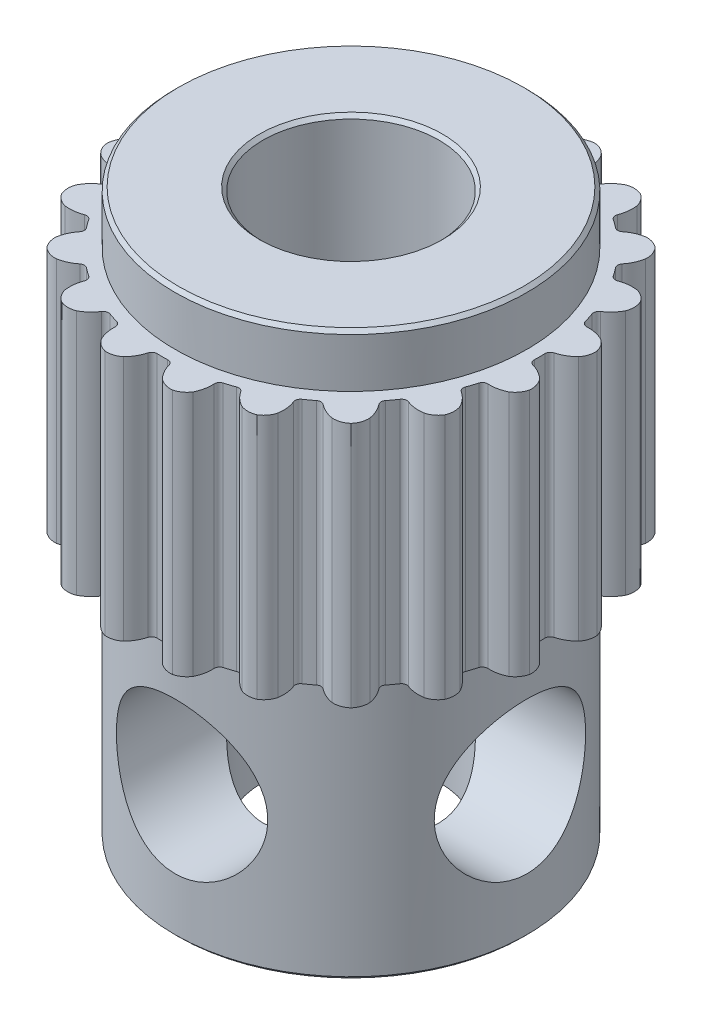
SolidWorks part; units mm, degrees
material "6061-T6 (SS)"
ref_plane "Front Plane" through (0, 0, 0) normal (0, 0, 1) x (1, 0, 0)
ref_plane "Top Plane" through (0, 0, 0) normal (0, 1, 0) x (1, 0, 0)
ref_plane "Right Plane" through (0, 0, 0) normal (1, 0, 0) x (0, 0, -1)
sketch "BodyS" plane through (0, 0, 0) normal (0, 0, 1) x (1, 0, 0)
  line L0 (6.11, -3.5) -> (6.11, 3.5)
  line L3 (6.11, 3.5) -> (2.5, 3.5)
  line L4 (2.5, 3.5) -> (2.5, -3.5)
  line L9 (2.5, -3.5) -> (6.11, -3.5)
  line L12 (0, 0) -> (6.11, 0) construction
  line L13 (0, 3.5) -> (0, -3.5) construction
  dimension "BoreDia" = 5
  dimension "Height" = 7
  dimension "BeltPathDiaControl" = 3.61
  dimension "RefBeltPathDia" = 12.22
revolve "Body" add sketch "BodyS" angle 360 about L13
sketch "GT2ProfileS" plane through (0, 0, 0) normal (0, 1, 0) x (1, 0, 0)
  line L1 (0, -6.11) -> (0, -5.36) construction
  line L2 (-0.9955, -6.0283) -> (-0.8733, -5.2884) construction
  line L3 (0, 0) -> (-0.8733, -5.2884) construction
  line L4 (0.9955, -6.0283) -> (0, 0) construction
  arc A3 (0.2997, -5.4688) -> (0.1507, -5.3579) centre (0.1549, -5.5078) ccw
  arc A4 (-0.9955, -6.0283) -> (0.9955, -6.0283) centre (0, 0) ccw
  arc A5 (-0.2997, -5.4688) -> (-0.1507, -5.3579) centre (-0.1549, -5.5078) cw
  arc A6 (-0.2997, -5.4688) -> (-0.5497, -5.907) centre (-1.2653, -5.2085) cw
  arc A8 (-0.1507, -5.3579) -> (0.1507, -5.3579) centre (0, 0) ccw
  arc A9 (-0.5497, -5.907) -> (-0.9955, -6.0283) centre (-0.9051, -5.4808) cw
  arc A10 (0.2997, -5.4688) -> (0.5497, -5.907) centre (1.2653, -5.2085) ccw
  arc A11 (0.5497, -5.907) -> (0.9955, -6.0283) centre (0.9051, -5.4808) ccw
  circle A12 centre (0, 0) radius 5.36 construction
  circle A13 centre (0, 0) radius 6.11 construction
  dimension "BottomRadius" = 0.15
  dimension "MidRadius" = 1
  dimension "TopRadius" = 0.555
  dimension "Height" = 0.75
  dimension "XDistMidRadius" = 0.4
  dimension "ArcLengthAngle" = 18.755
  dimension "ArcLength" = 2
extrude "GT2Profile" cut sketch "GT2ProfileS" along direction (0, -1, 0) on the side against the normal up to next (3.5 mm away) and the other way up to next (3.5 mm away)
pattern_circular "GT2 Groove CP" count 20 over 360 about axis through (0, 0, 0) along (0, 1, 0) of "GT2Profile"
sketch "TopWallS" plane through (0, 3.5, 0) normal (0, 1, 0) x (1, 0, 0)
  circle A0 centre (0, 0) radius 2.5 construction
  circle A1 centre (0, 0) radius 2.5
  circle A2 centre (0, 0) radius 5
  dimension "Thickness" = 2.5
extrude "TopWall" add sketch "TopWallS" along normal blind 1.5
sketch "BottomWallS" plane through (0, -3.5, 0) normal (0, -1, 0) x (-1, 0, 0)
  circle A0 centre (0, 0) radius 2.5
  circle A1 centre (0, 0) radius 2.5 construction
  circle A2 centre (0, 0) radius 5
  circle A3 centre (0, 0) radius 5 construction
extrude "BottomWall" add sketch "BottomWallS" along normal blind 7.5
ref_plane "ClearanceHolePlane" through (0, 0, 5) normal (0, 0, 1) x (1, 0, 0)
hole_wizard " Clearance Hole1" positions "Sketch1" profile "Sketch2" hole size "M4" standard "ANSI Metric"
sketch "Sketch1" plane through (0, 0, 5) normal (0, 0, 1) x (1, 0, 0)
  line L0 (0, -11) -> (0, -3.5) construction
  line L1 (-5, -11) -> (5, -11) construction
  line L2 (-0.1507, -3.5) -> (0.1507, -3.5) construction
  point P0 (0, -7.25)
sketch "Sketch2" plane through (0, -7.25, 5) normal (1, 0, 0) x (0, -1, 0)
  line L0 (0, 0) -> (0, 2.5)
  line L1 (0, 2.5) -> (2.15, 2.5)
  line L2 (2.15, 2.5) -> (2.15, 0)
  line L5 (2.15, 0) -> (0, 0)
  line L11 (0, -6.35) -> (0, 107.95) construction
  dimension "Thru Hole Dia." = 4.3
  dimension "Thru Hole Depth" = 2.5
pattern_circular "CirPattern1" count 2 every 90 about axis through (0, -11, 0) along (0, 1, 0) of " Clearance Hole1"
chamfer "InnerC" distance 0.1 angle 45 2 edges at (0, 5, 2.5) (0, -11, -2.5)
chamfer "OuterC" distance 0.1 angle 45 2 edges at (0, -11, -5) (0, 5, 5)
equation "\"D1@GT2 Groove CP\"=int(360/\"ArcLengthAngle@GT2ProfileS\")+1"
